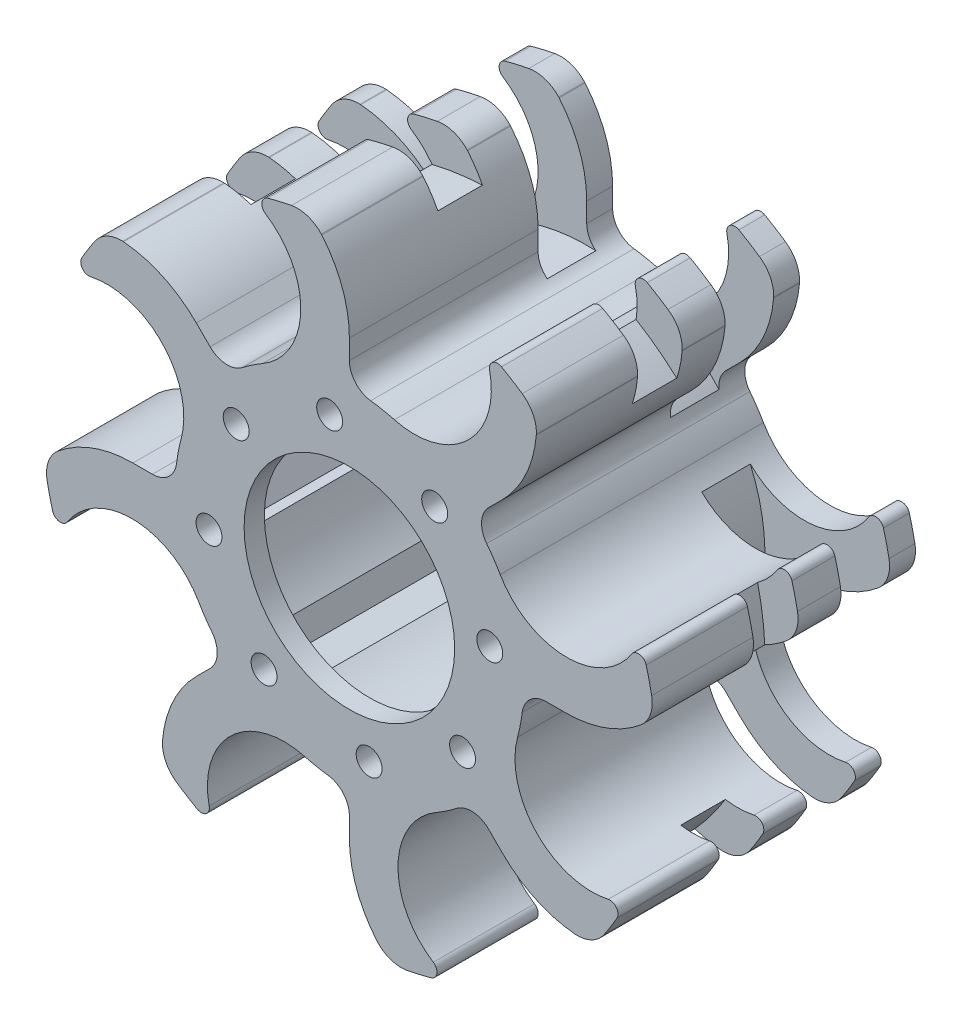
SolidWorks part; units mm, degrees
material "尼龙 101"
ref_plane "前视基准面" through (0, 0, 0) normal (0, 0, 1) x (1, 0, 0)
ref_plane "上视基准面" through (0, 0, 0) normal (0, 1, 0) x (1, 0, 0)
ref_plane "右视基准面" through (0, 0, 0) normal (1, 0, 0) x (0, 0, -1)
sketch "草图1" plane through (0, 0, 0) normal (0, 0, 1) x (1, 0, 0)
  line L0 (0, 0) -> (50000, 0) construction
  line L1 (0, 0) -> (0, -50000) construction
  line L2 (0, 0) -> (-10.75, 18.6195) construction
  line L3 (0, 21.5) -> (0, 26.7215)
  line L4 (-3.4, 36.0376) -> (32202.7815, -38210.0324) construction
  circle A0 centre (0, 0) radius 21.5
  arc A1 (0, 26.7215) -> (-3.4, 36.0376) centre (-14.4632, 26.7215) ccw
  arc A2 (-3.4, 36.0376) -> (-3.4606, 36.1064) centre (-4.9298, 34.7494) ccw
  arc A3 (-3.4606, 36.1064) -> (-7.1519, 37.3209) centre (-6.3991, 33.3924) ccw
  circle A4 centre (0, 0) radius 38 construction
  arc A5 (-7.1519, 37.3209) -> (-10.0801, 36.6387) centre (0, 0) ccw
  arc A6 (-10.0801, 36.6387) -> (-10.7994, 35.4998) centre (-9.8148, 35.6745) ccw
  arc A7 (-10.7994, 35.4998) -> (-10.3562, 34.8338) centre (-9.8148, 35.6745) ccw
  arc A8 (-10.3562, 34.8338) -> (-10.75, 18.6195) centre (-15.5, 26.8468) cw
  point P29 (0, 32)
  dimension "D1" = 43
  dimension "D3" = 76
  dimension "D5" = 2
  dimension "D6" = 4
  dimension "D7" = 40.1
  dimension "D8" = 1
  dimension "D9" = 1
  dimension "D11" = 9.5
  dimension "D2" = 30
  dimension "D4" = 3.4
  dimension "D10" = 0.8
  dimension "D12" = 32
extrude "凸台-拉伸1" add sketch "草图1" along normal blind 32.5 contours A7 A8 A0 L3 A1 A2 A3 A5 A6 | A0 A5
pattern_circular "阵列(圆周)1" count 8 over 360 about axis through (0, 0, 0) along (0, 0, 1) of "凸台-拉伸1"
fillet "圆角1" radius 3 8 edges at (15.2028, 15.2028, 16.25) (21.5, 0, 16.25) (15.2028, -15.2028, 16.25) (0, -21.5, 16.25) (-15.2028, -15.2028, 16.25) (-21.5, 0, 16.25) (-15.2028, 15.2028, 16.25) (0, 21.5, 16.25)
sketch "草图3" plane through (0, 0, 0) normal (0, 0, -1) x (-1, 0, 0)
  circle A0 centre (0, 0) radius 18.5
  dimension "D1" = 37
extrude "切除-拉伸1" cut sketch "草图3" against normal offset from surface (30 mm away) 2.5 up to face at (0, 0, 32.5)
sketch "草图4" plane through (0, 0, 32.5) normal (0, 0, 1) x (1, 0, 0)
  line L0 (0, 0) -> (50000, 0) construction
  line L1 (0, 0) -> (0, -50000) construction
  line L2 (-2.4355, 17.3297) -> (0, 0) construction
  circle A0 centre (0, 0) radius 17.5 construction
  circle A1 centre (-2.4355, 17.3297) radius 1.6
  circle A7 centre (0, 0) radius 13
  circle A8 centre (10.5318, 13.9761) radius 1.6
  circle A9 centre (17.3297, 2.4355) radius 1.6
  circle A10 centre (13.9761, -10.5318) radius 1.6
  circle A11 centre (2.4355, -17.3297) radius 1.6
  circle A12 centre (-10.5318, -13.9761) radius 1.6
  circle A13 centre (-17.3297, -2.4355) radius 1.6
  circle A14 centre (-13.9761, 10.5318) radius 1.6
  point P22 (0, 0)
  point P28 (0, 0)
  dimension "D1" = 35
  dimension "D2" = 3.2
  dimension "D5" = 26
  dimension "D3" = 8
  dimension "D4" = 8
extrude "切除-拉伸2" cut sketch "草图4" against normal blind 2.5
sketch "草图6" plane through (0, 0, 30) normal (0, 0, -1) x (-1, 0, 0)
  line L0 (2.4355, 20.6297) -> (2.4355, 14.0297) construction
  line L1 (2.4355, 20.6297) -> (-0.4224, 18.9797)
  line L2 (-0.4224, 18.9797) -> (-0.4224, 15.6797)
  line L3 (-0.4224, 15.6797) -> (2.4355, 14.0297)
  line L4 (2.4355, 14.0297) -> (5.2934, 15.6797)
  line L5 (5.2934, 15.6797) -> (5.2934, 18.9797)
  line L6 (5.2934, 18.9797) -> (2.4355, 20.6297)
  line L7 (16.3096, 12.8652) -> (13.122, 13.7193)
  line L8 (13.122, 13.7193) -> (10.7886, 11.3859)
  line L9 (10.7886, 11.3859) -> (11.6427, 8.1983)
  line L10 (11.6427, 8.1983) -> (14.8302, 7.3442)
  line L11 (14.8302, 7.3442) -> (17.1637, 9.6777)
  line L12 (17.1637, 9.6777) -> (16.3096, 12.8652)
  line L13 (20.6297, -2.4355) -> (18.9797, 0.4224)
  line L14 (18.9797, 0.4224) -> (15.6797, 0.4224)
  line L15 (15.6797, 0.4224) -> (14.0297, -2.4355)
  line L16 (14.0297, -2.4355) -> (15.6797, -5.2934)
  line L17 (15.6797, -5.2934) -> (18.9797, -5.2934)
  line L18 (18.9797, -5.2934) -> (20.6297, -2.4355)
  line L19 (12.8652, -16.3096) -> (13.7193, -13.122)
  line L20 (13.7193, -13.122) -> (11.3859, -10.7886)
  line L21 (11.3859, -10.7886) -> (8.1983, -11.6427)
  line L22 (8.1983, -11.6427) -> (7.3442, -14.8302)
  line L23 (7.3442, -14.8302) -> (9.6777, -17.1637)
  line L24 (9.6777, -17.1637) -> (12.8652, -16.3096)
  line L25 (-2.4355, -20.6297) -> (0.4224, -18.9797)
  line L26 (0.4224, -18.9797) -> (0.4224, -15.6797)
  line L27 (0.4224, -15.6797) -> (-2.4355, -14.0297)
  line L28 (-2.4355, -14.0297) -> (-5.2934, -15.6797)
  line L29 (-5.2934, -15.6797) -> (-5.2934, -18.9797)
  line L30 (-5.2934, -18.9797) -> (-2.4355, -20.6297)
  line L31 (-16.3096, -12.8652) -> (-13.122, -13.7193)
  line L32 (-13.122, -13.7193) -> (-10.7886, -11.3859)
  line L33 (-10.7886, -11.3859) -> (-11.6427, -8.1983)
  line L34 (-11.6427, -8.1983) -> (-14.8302, -7.3442)
  line L35 (-14.8302, -7.3442) -> (-17.1637, -9.6777)
  line L36 (-17.1637, -9.6777) -> (-16.3096, -12.8652)
  line L37 (-20.6297, 2.4355) -> (-18.9797, -0.4224)
  line L38 (-18.9797, -0.4224) -> (-15.6797, -0.4224)
  line L39 (-15.6797, -0.4224) -> (-14.0297, 2.4355)
  line L40 (-14.0297, 2.4355) -> (-15.6797, 5.2934)
  line L41 (-15.6797, 5.2934) -> (-18.9797, 5.2934)
  line L42 (-18.9797, 5.2934) -> (-20.6297, 2.4355)
  line L43 (-12.8652, 16.3096) -> (-13.7193, 13.122)
  line L44 (-13.7193, 13.122) -> (-11.3859, 10.7886)
  line L45 (-11.3859, 10.7886) -> (-8.1983, 11.6427)
  line L46 (-8.1983, 11.6427) -> (-7.3442, 14.8302)
  line L47 (-7.3442, 14.8302) -> (-9.6777, 17.1637)
  line L48 (-9.6777, 17.1637) -> (-12.8652, 16.3096)
  circle A0 centre (2.4355, 17.3297) radius 2.8579 construction
  point P54 (0, 0)
  dimension "D1" = 6.6
  dimension "D2" = 8
extrude "切除-拉伸4" cut sketch "草图6" along normal up to next
sketch "草图7" plane through (0, 0, 0) normal (0, 1, 0) x (1, 0, 0)
  line L0 (34.8338, 0) -> (18.6195, 0) construction
  line L1 (22, -9.2) -> (42, -9.2)
  line L2 (22, -9.2) -> (22, -3.2)
  line L3 (22, -3.2) -> (42, -3.2)
  line L4 (42, -9.2) -> (42, -3.2)
  line L5 (22, -9.2) -> (42, -3.2) construction
  line L6 (22, -3.2) -> (42, -9.2) construction
  line L7 (0, 0) -> (0, 50000) construction
  line L8 (37.3209, -32.5) -> (37.3209, 0) construction
  line L9 (33.3209, -20) -> (43.3209, -20)
  line L10 (33.3209, -20) -> (33.3209, -14.5)
  line L11 (33.3209, -14.5) -> (43.3209, -14.5)
  line L12 (43.3209, -20) -> (43.3209, -14.5)
  line L13 (33.3209, -20) -> (43.3209, -14.5) construction
  line L14 (33.3209, -14.5) -> (43.3209, -20) construction
  point P0 (32, -6.2)
  point P11 (38.3209, -17.25)
  dimension "D1" = 3.2
  dimension "D2" = 22
  dimension "D3" = 6
  dimension "D4" = 20
  dimension "D5" = 12.5
  dimension "D6" = 4
  dimension "D7" = 10
  dimension "D8" = 5.5
revolve "切除-旋转1" cut sketch "草图7" angle 360 about L7
